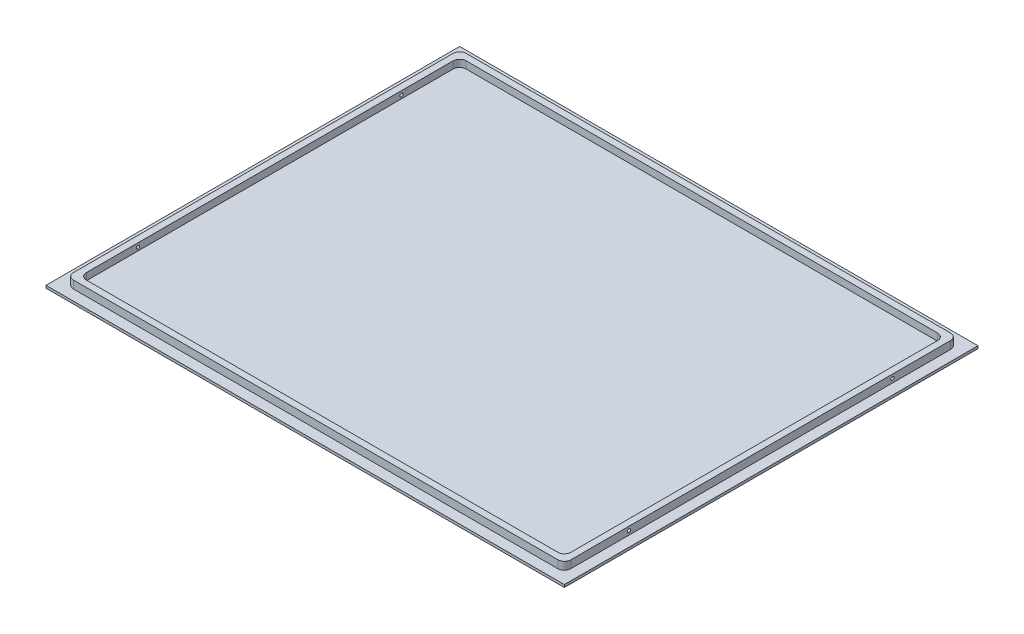
SolidWorks part; units mm, degrees
material "7079 Alloy"
ref_plane "Front Plane" through (0, 0, 0) normal (0, 0, 1) x (1, 0, 0)
ref_plane "Top Plane" through (0, 0, 0) normal (0, 1, 0) x (1, 0, 0)
ref_plane "Right Plane" through (0, 0, 0) normal (1, 0, 0) x (0, 0, -1)
sketch "Sketch1" plane through (0, 0, 0) normal (0, 1, 0) x (1, 0, 0)
  line L0 (-200.5, 0) -> (0, 0) construction
  line L1 (-200.5, 160) -> (200.5, 160)
  line L2 (-200.5, 160) -> (-200.5, -160)
  line L3 (-200.5, -160) -> (200.5, -160)
  line L4 (200.5, 160) -> (200.5, -160)
  line L5 (0, 0) -> (0, 160) construction
  dimension "D1" = 320
  dimension "D2" = 401
extrude "Extrude1" add sketch "Sketch1" along normal blind 8
sketch "Sketch2" plane through (0, 8, 0) normal (0, 1, 0) x (1, 0, 0)
  line L0 (-200.5, 160) -> (-200.5, -160) construction
  line L1 (-192.4, 151.9) -> (192.4, 151.9)
  line L2 (-192.4, 151.9) -> (-192.4, -151.9)
  line L3 (-192.4, -151.9) -> (192.4, -151.9)
  line L4 (192.4, 151.9) -> (192.4, -151.9)
  line L5 (-192.4, 151.9) -> (192.4, -151.9) construction
  line L6 (-192.4, -151.9) -> (192.4, 151.9) construction
  line L7 (-200.5, -160) -> (200.5, -160) construction
  line L8 (200.5, -160) -> (200.5, 160) construction
  line L9 (200.5, 160) -> (-200.5, 160) construction
  line L10 (-200.5, 160) -> (-200.5, -160)
  line L11 (-200.5, -160) -> (200.5, -160)
  line L12 (200.5, -160) -> (200.5, 160)
  line L13 (200.5, 160) -> (-200.5, 160)
  point P0 (0, 0)
  dimension "D1" = 8.1
  dimension "D2" = 8.1
extrude "Cut-Extrude1" cut sketch "Sketch2" against normal blind 6
sketch "Sketch3" plane through (0, 8, 0) normal (0, 1, 0) x (1, 0, 0)
  line L0 (192.4, -151.9) -> (192.4, 151.9) construction
  line L1 (187.4, -146.9) -> (-187.4, -146.9)
  line L2 (187.4, -146.9) -> (187.4, 146.9)
  line L3 (187.4, 146.9) -> (-187.4, 146.9)
  line L4 (-187.4, -146.9) -> (-187.4, 146.9)
  line L5 (187.4, -146.9) -> (-187.4, 146.9) construction
  line L6 (187.4, 146.9) -> (-187.4, -146.9) construction
  line L7 (-192.4, -151.9) -> (192.4, -151.9) construction
  point P0 (0, 0)
  dimension "D1" = 5
  dimension "D2" = 5
extrude "Cut-Extrude2" cut sketch "Sketch3" against normal blind 5.5
fillet "Fillet1" radius 5 8 edges at (187.4, 5.25, 146.9) (-187.4, 5.25, 146.9) (-187.4, 5.25, -146.9) (187.4, 5.25, -146.9) (192.4, 5, 151.9) (192.4, 5, -151.9) (-192.4, 5, -151.9) (-192.4, 5, 151.9)
sketch "Sketch4" plane through (-192.4, 0, 0) normal (-1, 0, 0) x (0, 0, 1)
  line L0 (-151.9, 5) -> (0, 5) construction
  line L1 (-151.9, 2) -> (-151.9, 8) construction
  line L2 (0, 5) -> (0, 2) construction
  line L3 (-146.9, 2) -> (146.9, 2) construction
  circle A0 centre (-101.9, 5) radius 1.25
  circle A1 centre (101.9, 5) radius 1.25
  dimension "D1" = 2.5
  dimension "D2" = 50
extrude "Cut-Extrude3" cut sketch "Sketch4" against normal through all
